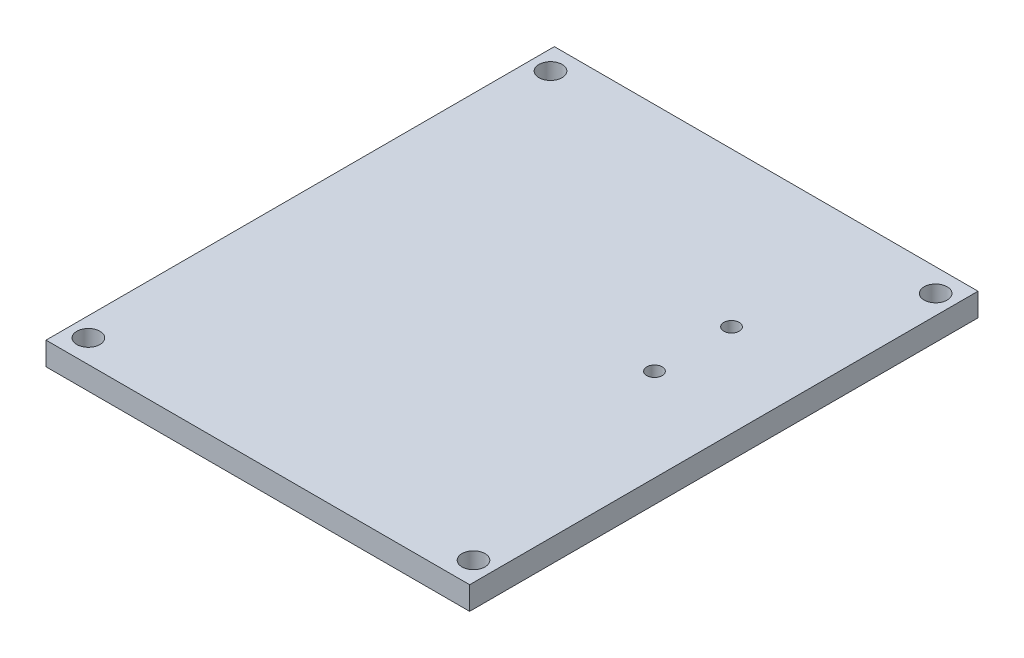
SolidWorks part; units mm, degrees
ref_plane "Plan de face" through (0, 0, 0) normal (0, 0, 1) x (1, 0, 0)
ref_plane "Plan de dessus" through (0, 0, 0) normal (0, 1, 0) x (1, 0, 0)
ref_plane "Plan de droite" through (0, 0, 0) normal (1, 0, 0) x (0, 0, -1)
sketch "Esquisse1" plane through (0, 0, 0) normal (0, 1, 0) x (1, 0, 0)
  line L0 (-27.5396, -33.0827) -> (27.4604, -33.0827)
  line L1 (-27.5396, -33.0827) -> (-27.5396, 32.9173)
  line L2 (-27.5396, 32.9173) -> (27.4604, 32.9173)
  line L3 (27.4604, -33.0827) -> (27.4604, 32.9173)
  line L4 (-27.5396, -33.0827) -> (27.4604, 32.9173) construction
  line L5 (-27.5396, 32.9173) -> (27.4604, -33.0827) construction
  line L6 (-25.0396, -30.0827) -> (24.9604, 29.9173) construction
  line L7 (-25.0396, 29.9173) -> (24.9604, -30.0827) construction
  line L8 (27.4604, 12.9173) -> (15.4604, 12.9173) construction
  line L9 (15.4604, 12.9173) -> (15.4604, 2.9173) construction
  line L10 (27.4604, 32.9173) -> (27.4604, 12.9173) construction
  circle A0 centre (-25.0396, 29.9173) radius 1.5
  circle A1 centre (24.9604, 29.9173) radius 1.5
  circle A2 centre (24.9604, -30.0827) radius 1.5
  circle A3 centre (-25.0396, -30.0827) radius 1.5
  circle A4 centre (15.4604, 12.9173) radius 1
  circle A5 centre (15.4604, 2.9173) radius 1
  point P0 (-0.0396, -0.0827)
  point P5 (-0.0396, -0.0827)
  dimension "D1" = 12
  dimension "D2" = 20
extrude "Boss.-Extru.1" add sketch "Esquisse1" along normal blind 3
